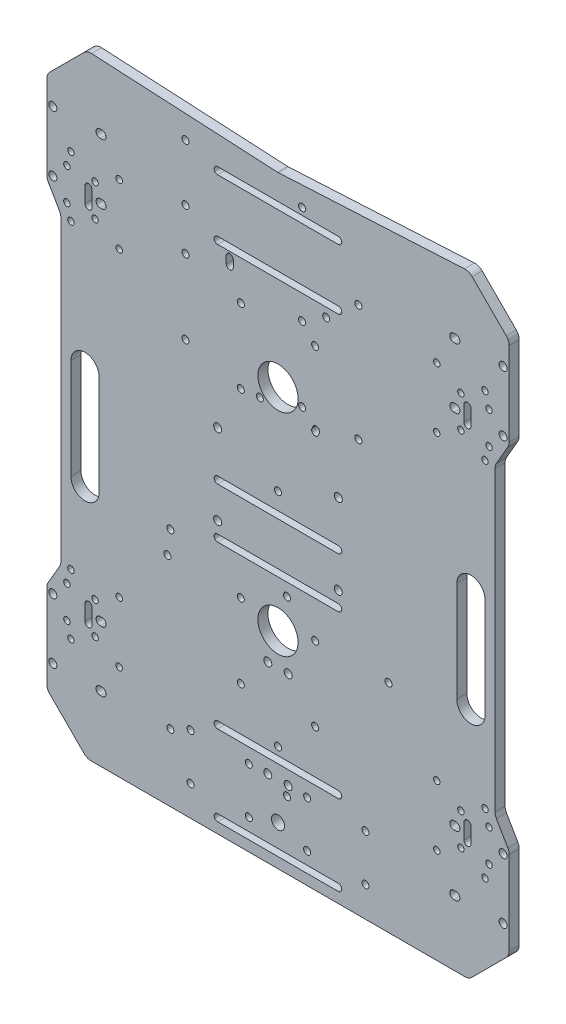
SolidWorks part; units mm, degrees
material "PMMA"
ref_plane "前视基准面" through (0, 0, 0) normal (0, 0, 1) x (1, 0, 0)
ref_plane "上视基准面" through (0, 0, 0) normal (0, 1, 0) x (1, 0, 0)
ref_plane "右视基准面" through (0, 0, 0) normal (1, 0, 0) x (0, 0, -1)
sketch "草图1" plane through (0, 0, 0) normal (0, 0, 1) x (1, 0, 0)
  line L0 (87.5, -88) -> (88.5, -88)
  line L1 (88.5, -92) -> (87.5, -92)
  line L2 (87.5, -118) -> (88.5, -118)
  line L3 (88.5, -122) -> (87.5, -122)
  line L4 (-87.5, -88) -> (-88.5, -88)
  line L5 (-88.5, -92) -> (-87.5, -92)
  line L6 (-87.5, -118) -> (-88.5, -118)
  line L7 (-88.5, -122) -> (-87.5, -122)
  line L8 (-87.5, 88) -> (-88.5, 88)
  line L9 (-88.5, 92) -> (-87.5, 92)
  line L10 (-87.5, 118) -> (-88.5, 118)
  line L11 (-88.5, 122) -> (-87.5, 122)
  line L12 (30, -26.75) -> (-30, -26.75)
  line L13 (-30, -23.25) -> (30, -23.25)
  line L14 (30, 131.5) -> (-30, 131.5)
  line L15 (-30, 135) -> (30, 135)
  line L16 (30, -147.25) -> (-30, -147.25)
  line L17 (-30, -143.75) -> (30, -143.75)
  line L18 (30, 101.5) -> (-30, 101.5)
  line L19 (-30, 105) -> (30, 105)
  line L20 (30, -1.75) -> (-30, -1.75)
  line L21 (-30, 1.75) -> (30, 1.75)
  line L22 (30, -107.25) -> (-30, -107.25)
  line L23 (-30, -103.75) -> (30, -103.75)
  line L24 (-25.75, 95.308) -> (-25.75, 98.808)
  line L25 (-22.25, 98.808) -> (-22.25, 95.308)
  line L26 (-89, 15) -> (-89, -35)
  line L27 (-103, -35) -> (-103, 15)
  line L28 (-96, -86.1) -> (-96, -93.9)
  line L29 (-92.5, -93.9) -> (-92.5, -86.1)
  line L30 (-96, 93.9) -> (-96, 86.1)
  line L31 (-92.5, 86.1) -> (-92.5, 93.9)
  line L32 (96, -86.1) -> (96, -93.9)
  line L33 (92.5, -93.9) -> (92.5, -86.1)
  line L34 (96, 93.9) -> (96, 86.1)
  line L35 (92.5, 86.1) -> (92.5, 93.9)
  line L36 (113.5355, -133.9645) -> (96.4645, -151.0355)
  line L37 (92.9289, -152.5) -> (-92.9289, -152.5)
  line L38 (-96.4645, -151.0355) -> (-113.5355, -133.9645)
  line L39 (-115, -130.4289) -> (-115, -88.8397)
  line L40 (-108.6699, -76.5359) -> (-114.3301, -86.3397)
  line L41 (-108, 74.0359) -> (-108, -74.0359)
  line L42 (-114.3301, 86.3397) -> (-108.6699, 76.5359)
  line L43 (-115, 88.8397) -> (-115, 130.4289)
  line L44 (-113.5355, 133.9645) -> (-96.5746, 150.9254)
  line L45 (-0.2628, 147.5138) -> (-92.7763, 152.383)
  line L46 (92.7763, 152.383) -> (0.2628, 147.5138)
  line L47 (96.5746, 150.9254) -> (113.5355, 133.9645)
  line L48 (115, 130.4289) -> (115, 88.8397)
  line L49 (114.3301, 86.3397) -> (108.6699, 76.5359)
  line L50 (108, 74.0359) -> (108, -74.0359)
  line L51 (108.6699, -76.5359) -> (114.3301, -86.3397)
  line L52 (115, -88.8397) -> (115, -130.4289)
  line L53 (89, 15) -> (89, -35)
  line L54 (103, -35) -> (103, 15)
  line L55 (87.5, 118) -> (88.5, 118)
  line L56 (88.5, 122) -> (87.5, 122)
  line L57 (87.5, 88) -> (88.5, 88)
  line L58 (88.5, 92) -> (87.5, 92)
  arc A0 (112, -118) -> (112, -122) centre (112, -120) cw
  arc A1 (112, -122) -> (112, -118) centre (112, -120) cw
  arc A2 (88.5, -88) -> (88.5, -92) centre (88.5, -90) cw
  arc A3 (87.5, -92) -> (87.5, -88) centre (87.5, -90) cw
  arc A4 (88.5, -118) -> (88.5, -122) centre (88.5, -120) cw
  arc A5 (87.5, -122) -> (87.5, -118) centre (87.5, -120) cw
  arc A6 (112, -88) -> (112, -92) centre (112, -90) cw
  arc A7 (112, -92) -> (112, -88) centre (112, -90) cw
  arc A8 (-88.5, -88) -> (-88.5, -92) centre (-88.5, -90) ccw
  arc A9 (-87.5, -92) -> (-87.5, -88) centre (-87.5, -90) ccw
  arc A10 (-88.5, -118) -> (-88.5, -122) centre (-88.5, -120) ccw
  arc A11 (-87.5, -122) -> (-87.5, -118) centre (-87.5, -120) ccw
  arc A12 (112, 122) -> (112, 118) centre (112, 120) ccw
  arc A13 (112, 118) -> (112, 122) centre (112, 120) ccw
  arc A14 (112, 92) -> (112, 88) centre (112, 90) ccw
  arc A15 (112, 88) -> (112, 92) centre (112, 90) ccw
  arc A16 (-112, 122) -> (-112, 118) centre (-112, 120) cw
  arc A17 (-112, 118) -> (-112, 122) centre (-112, 120) cw
  arc A18 (-88.5, 88) -> (-88.5, 92) centre (-88.5, 90) cw
  arc A19 (-87.5, 92) -> (-87.5, 88) centre (-87.5, 90) cw
  arc A20 (-88.5, 118) -> (-88.5, 122) centre (-88.5, 120) cw
  arc A21 (-87.5, 122) -> (-87.5, 118) centre (-87.5, 120) cw
  arc A22 (-112, 92) -> (-112, 88) centre (-112, 90) cw
  arc A23 (-112, 88) -> (-112, 92) centre (-112, 90) cw
  arc A24 (0, -129.25) -> (0, -135.75) centre (0, -132.5) cw
  arc A25 (0, -135.75) -> (0, -129.25) centre (0, -132.5) cw
  arc A26 (-30, -26.75) -> (-30, -23.25) centre (-30, -25) cw
  arc A27 (30, -23.25) -> (30, -26.75) centre (30, -25) cw
  arc A28 (-30, 131.5) -> (-30, 135) centre (-30, 133.25) cw
  arc A29 (30, 135) -> (30, 131.5) centre (30, 133.25) cw
  arc A30 (-30, -147.25) -> (-30, -143.75) centre (-30, -145.5) cw
  arc A31 (30, -143.75) -> (30, -147.25) centre (30, -145.5) cw
  arc A32 (-30, 101.5) -> (-30, 105) centre (-30, 103.25) cw
  arc A33 (30, 105) -> (30, 101.5) centre (30, 103.25) cw
  arc A34 (-30, -1.75) -> (-30, 1.75) centre (-30, 0) cw
  arc A35 (30, 1.75) -> (30, -1.75) centre (30, 0) cw
  arc A36 (-30, -107.25) -> (-30, -103.75) centre (-30, -105.5) cw
  arc A37 (30, -103.75) -> (30, -107.25) centre (30, -105.5) cw
  arc A38 (55, -43.08) -> (55, -46.58) centre (55, -44.83) cw
  arc A39 (55, -46.58) -> (55, -43.08) centre (55, -44.83) cw
  arc A40 (0, 11.92) -> (0, 8.42) centre (0, 10.17) cw
  arc A41 (0, 8.42) -> (0, 11.92) centre (0, 10.17) cw
  arc A42 (-55, -43.08) -> (-55, -46.58) centre (-55, -44.83) cw
  arc A43 (-55, -46.58) -> (-55, -43.08) centre (-55, -44.83) cw
  arc A44 (5.075, -63.9) -> (5.075, -67.9) centre (5.075, -65.9) cw
  arc A45 (5.075, -67.9) -> (5.075, -63.9) centre (5.075, -65.9) cw
  arc A46 (-5.075, -63.9) -> (-5.075, -67.9) centre (-5.075, -65.9) cw
  arc A47 (-5.075, -67.9) -> (-5.075, -63.9) centre (-5.075, -65.9) cw
  arc A48 (-5.075, -112.1) -> (-5.075, -116.1) centre (-5.075, -114.1) cw
  arc A49 (-5.075, -116.1) -> (-5.075, -112.1) centre (-5.075, -114.1) cw
  arc A50 (5.075, -112.1) -> (5.075, -116.1) centre (5.075, -114.1) cw
  arc A51 (5.075, -116.1) -> (5.075, -112.1) centre (5.075, -114.1) cw
  arc A52 (0, -98.08) -> (0, -101.58) centre (0, -99.83) cw
  arc A53 (0, -101.58) -> (0, -98.08) centre (0, -99.83) cw
  arc A54 (-43.5, -112.75) -> (-43.5, -116.25) centre (-43.5, -114.5) cw
  arc A55 (-43.5, -116.25) -> (-43.5, -112.75) centre (-43.5, -114.5) cw
  arc A56 (43.5, -112.75) -> (43.5, -116.25) centre (43.5, -114.5) cw
  arc A57 (43.5, -116.25) -> (43.5, -112.75) centre (43.5, -114.5) cw
  arc A58 (-43.5, -135.75) -> (-43.5, -139.25) centre (-43.5, -137.5) cw
  arc A59 (-43.5, -139.25) -> (-43.5, -135.75) centre (-43.5, -137.5) cw
  arc A60 (43.5, -135.75) -> (43.5, -139.25) centre (43.5, -137.5) cw
  arc A61 (43.5, -139.25) -> (43.5, -135.75) centre (43.5, -137.5) cw
  arc A62 (14.5, -135.75) -> (14.5, -139.25) centre (14.5, -137.5) cw
  arc A63 (14.5, -139.25) -> (14.5, -135.75) centre (14.5, -137.5) cw
  arc A64 (-14.5, -112.75) -> (-14.5, -116.25) centre (-14.5, -114.5) cw
  arc A65 (-14.5, -116.25) -> (-14.5, -112.75) centre (-14.5, -114.5) cw
  arc A66 (14.5, -112.75) -> (14.5, -116.25) centre (14.5, -114.5) cw
  arc A67 (14.5, -116.25) -> (14.5, -112.75) centre (14.5, -114.5) cw
  arc A68 (-14.5, -135.75) -> (-14.5, -139.25) centre (-14.5, -137.5) cw
  arc A69 (-14.5, -139.25) -> (-14.5, -135.75) centre (-14.5, -137.5) cw
  arc A70 (-18.5, 80.25) -> (-18.5, 83.75) centre (-18.5, 82) cw
  arc A71 (-18.5, 83.75) -> (-18.5, 80.25) centre (-18.5, 82) cw
  arc A72 (-18.5, 43.25) -> (-18.5, 46.75) centre (-18.5, 45) cw
  arc A73 (-18.5, 46.75) -> (-18.5, 43.25) centre (-18.5, 45) cw
  arc A74 (18.5, 80.25) -> (18.5, 83.75) centre (18.5, 82) cw
  arc A75 (18.5, 83.75) -> (18.5, 80.25) centre (18.5, 82) cw
  arc A76 (-18.5, -83.75) -> (-18.5, -80.25) centre (-18.5, -82) ccw
  arc A77 (-18.5, -80.25) -> (-18.5, -83.75) centre (-18.5, -82) ccw
  arc A78 (18.5, -46.75) -> (18.5, -43.25) centre (18.5, -45) ccw
  arc A79 (18.5, -43.25) -> (18.5, -46.75) centre (18.5, -45) ccw
  arc A80 (-18.5, -46.75) -> (-18.5, -43.25) centre (-18.5, -45) ccw
  arc A81 (-18.5, -43.25) -> (-18.5, -46.75) centre (-18.5, -45) ccw
  arc A82 (18.5, -83.75) -> (18.5, -80.25) centre (18.5, -82) ccw
  arc A83 (18.5, -80.25) -> (18.5, -83.75) centre (18.5, -82) ccw
  arc A84 (-25.75, 98.808) -> (-24, 100.558) centre (-24, 98.808) cw
  arc A85 (-22.25, 95.308) -> (-25.75, 95.308) centre (-24, 95.308) cw
  arc A86 (-24, 100.558) -> (-22.25, 98.808) centre (-24, 98.808) cw
  arc A87 (17.2588, 46.2337) -> (19, 47.808) centre (19, 46.058) cw
  arc A88 (18.5, 43.25) -> (17.2588, 46.2337) centre (18.5, 45) cw
  arc A89 (20.2412, 44.8243) -> (18.5, 43.25) centre (18.5, 45) cw
  arc A90 (19, 47.808) -> (20.2412, 44.8243) centre (19, 46.058) cw
  arc A91 (-9, 47.808) -> (-9, 44.308) centre (-9, 46.058) cw
  arc A92 (-9, 44.308) -> (-9, 47.808) centre (-9, 46.058) cw
  arc A93 (24, 98.808) -> (24, 95.308) centre (24, 97.058) cw
  arc A94 (24, 95.308) -> (24, 98.808) centre (24, 97.058) cw
  arc A95 (0, -60) -> (0, -40) centre (0, -50) ccw
  arc A96 (0, -40) -> (0, -60) centre (0, -50) ccw
  arc A97 (0, 45) -> (0, 65) centre (0, 55) ccw
  arc A98 (0, 65) -> (0, 45) centre (0, 55) ccw
  arc A99 (-53.5, -31.25) -> (-53.5, -34.75) centre (-53.5, -33) cw
  arc A100 (-53.5, -34.75) -> (-53.5, -31.25) centre (-53.5, -33) cw
  arc A101 (4.5, -31.25) -> (4.5, -34.75) centre (4.5, -33) cw
  arc A102 (4.5, -34.75) -> (4.5, -31.25) centre (4.5, -33) cw
  arc A103 (4.5, -117.25) -> (4.5, -120.75) centre (4.5, -119) cw
  arc A104 (4.5, -120.75) -> (4.5, -117.25) centre (4.5, -119) cw
  arc A105 (-53.5, -117.25) -> (-53.5, -120.75) centre (-53.5, -119) cw
  arc A106 (-53.5, -120.75) -> (-53.5, -117.25) centre (-53.5, -119) cw
  arc A107 (-89, -35) -> (-103, -35) centre (-96, -35) cw
  arc A108 (-96, 22) -> (-89, 15) centre (-96, 15) cw
  arc A109 (-103, 15) -> (-96, 22) centre (-96, 15) cw
  arc A110 (12, 91.25) -> (12, 87.75) centre (12, 89.5) cw
  arc A111 (12, 87.75) -> (12, 91.25) centre (12, 89.5) cw
  arc A112 (-46, 91.25) -> (-46, 87.75) centre (-46, 89.5) cw
  arc A113 (-46, 87.75) -> (-46, 91.25) centre (-46, 89.5) cw
  arc A114 (12, 140.25) -> (12, 136.75) centre (12, 138.5) cw
  arc A115 (12, 136.75) -> (12, 140.25) centre (12, 138.5) cw
  arc A116 (-46, 140.25) -> (-46, 136.75) centre (-46, 138.5) cw
  arc A117 (-46, 136.75) -> (-46, 140.25) centre (-46, 138.5) cw
  arc A118 (40, 54.25) -> (40, 50.75) centre (40, 52.5) cw
  arc A119 (40, 50.75) -> (40, 54.25) centre (40, 52.5) cw
  arc A120 (-46, 112.25) -> (-46, 108.75) centre (-46, 110.5) cw
  arc A121 (-46, 108.75) -> (-46, 112.25) centre (-46, 110.5) cw
  arc A122 (40, 112.25) -> (40, 108.75) centre (40, 110.5) cw
  arc A123 (40, 108.75) -> (40, 112.25) centre (40, 110.5) cw
  arc A124 (12, 54.25) -> (12, 50.75) centre (12, 52.5) cw
  arc A125 (12, 50.75) -> (12, 54.25) centre (12, 52.5) cw
  arc A126 (-46, 54.25) -> (-46, 50.75) centre (-46, 52.5) cw
  arc A127 (-46, 50.75) -> (-46, 54.25) centre (-46, 52.5) cw
  arc A128 (30, -15.5) -> (30, -19.5) centre (30, -17.5) cw
  arc A129 (30, -19.5) -> (30, -15.5) centre (30, -17.5) cw
  arc A130 (-30, 24.5) -> (-30, 20.5) centre (-30, 22.5) cw
  arc A131 (-30, 20.5) -> (-30, 24.5) centre (-30, 22.5) cw
  arc A132 (30, 24.5) -> (30, 20.5) centre (30, 22.5) cw
  arc A133 (30, 20.5) -> (30, 24.5) centre (30, 22.5) cw
  arc A134 (-30, -15.5) -> (-30, -19.5) centre (-30, -17.5) cw
  arc A135 (-30, -19.5) -> (-30, -15.5) centre (-30, -17.5) cw
  arc A136 (-91, -96.4) -> (-91, -99.6) centre (-91, -98) ccw
  arc A137 (-91, -99.6) -> (-91, -96.4) centre (-91, -98) ccw
  arc A138 (-91, -80.4) -> (-91, -83.6) centre (-91, -82) ccw
  arc A139 (-91, -83.6) -> (-91, -80.4) centre (-91, -82) ccw
  arc A140 (-105, -80.4) -> (-105, -83.6) centre (-105, -82) ccw
  arc A141 (-105, -83.6) -> (-105, -80.4) centre (-105, -82) ccw
  arc A142 (-96, -93.9) -> (-92.5, -93.9) centre (-94.25, -93.9) ccw
  arc A143 (-92.5, -86.1) -> (-94.25, -84.35) centre (-94.25, -86.1) ccw
  arc A144 (-94.25, -84.35) -> (-96, -86.1) centre (-94.25, -86.1) ccw
  arc A145 (-79, -103.4) -> (-79, -106.6) centre (-79, -105) ccw
  arc A146 (-79, -106.6) -> (-79, -103.4) centre (-79, -105) ccw
  arc A147 (-103, -73.4) -> (-103, -76.6) centre (-103, -75) ccw
  arc A148 (-103, -76.6) -> (-103, -73.4) centre (-103, -75) ccw
  arc A149 (-103, -103.4) -> (-103, -106.6) centre (-103, -105) ccw
  arc A150 (-103, -106.6) -> (-103, -103.4) centre (-103, -105) ccw
  arc A151 (-105, -96.4) -> (-105, -99.6) centre (-105, -98) ccw
  arc A152 (-105, -99.6) -> (-105, -96.4) centre (-105, -98) ccw
  arc A153 (-79, -73.4) -> (-79, -76.6) centre (-79, -75) ccw
  arc A154 (-79, -76.6) -> (-79, -73.4) centre (-79, -75) ccw
  arc A155 (-91, 83.6) -> (-91, 80.4) centre (-91, 82) ccw
  arc A156 (-91, 80.4) -> (-91, 83.6) centre (-91, 82) ccw
  arc A157 (-91, 99.6) -> (-91, 96.4) centre (-91, 98) ccw
  arc A158 (-91, 96.4) -> (-91, 99.6) centre (-91, 98) ccw
  arc A159 (-105, 99.6) -> (-105, 96.4) centre (-105, 98) ccw
  arc A160 (-105, 96.4) -> (-105, 99.6) centre (-105, 98) ccw
  arc A161 (-96, 86.1) -> (-92.5, 86.1) centre (-94.25, 86.1) ccw
  arc A162 (-92.5, 93.9) -> (-94.25, 95.65) centre (-94.25, 93.9) ccw
  arc A163 (-94.25, 95.65) -> (-96, 93.9) centre (-94.25, 93.9) ccw
  arc A164 (-79, 76.6) -> (-79, 73.4) centre (-79, 75) ccw
  arc A165 (-79, 73.4) -> (-79, 76.6) centre (-79, 75) ccw
  arc A166 (-103, 106.6) -> (-103, 103.4) centre (-103, 105) ccw
  arc A167 (-103, 103.4) -> (-103, 106.6) centre (-103, 105) ccw
  arc A168 (-103, 76.6) -> (-103, 73.4) centre (-103, 75) ccw
  arc A169 (-103, 73.4) -> (-103, 76.6) centre (-103, 75) ccw
  arc A170 (-105, 83.6) -> (-105, 80.4) centre (-105, 82) ccw
  arc A171 (-105, 80.4) -> (-105, 83.6) centre (-105, 82) ccw
  arc A172 (-79, 106.6) -> (-79, 103.4) centre (-79, 105) ccw
  arc A173 (-79, 103.4) -> (-79, 106.6) centre (-79, 105) ccw
  arc A174 (91, -96.4) -> (91, -99.6) centre (91, -98) cw
  arc A175 (91, -99.6) -> (91, -96.4) centre (91, -98) cw
  arc A176 (91, -80.4) -> (91, -83.6) centre (91, -82) cw
  arc A177 (91, -83.6) -> (91, -80.4) centre (91, -82) cw
  arc A178 (105, -80.4) -> (105, -83.6) centre (105, -82) cw
  arc A179 (105, -83.6) -> (105, -80.4) centre (105, -82) cw
  arc A180 (96, -93.9) -> (92.5, -93.9) centre (94.25, -93.9) cw
  arc A181 (94.25, -84.35) -> (96, -86.1) centre (94.25, -86.1) cw
  arc A182 (92.5, -86.1) -> (94.25, -84.35) centre (94.25, -86.1) cw
  arc A183 (79, -103.4) -> (79, -106.6) centre (79, -105) cw
  arc A184 (79, -106.6) -> (79, -103.4) centre (79, -105) cw
  arc A185 (103, -73.4) -> (103, -76.6) centre (103, -75) cw
  arc A186 (103, -76.6) -> (103, -73.4) centre (103, -75) cw
  arc A187 (103, -103.4) -> (103, -106.6) centre (103, -105) cw
  arc A188 (103, -106.6) -> (103, -103.4) centre (103, -105) cw
  arc A189 (105, -96.4) -> (105, -99.6) centre (105, -98) cw
  arc A190 (105, -99.6) -> (105, -96.4) centre (105, -98) cw
  arc A191 (79, -73.4) -> (79, -76.6) centre (79, -75) cw
  arc A192 (79, -76.6) -> (79, -73.4) centre (79, -75) cw
  arc A193 (91, 83.6) -> (91, 80.4) centre (91, 82) cw
  arc A194 (91, 80.4) -> (91, 83.6) centre (91, 82) cw
  arc A195 (91, 99.6) -> (91, 96.4) centre (91, 98) cw
  arc A196 (91, 96.4) -> (91, 99.6) centre (91, 98) cw
  arc A197 (105, 99.6) -> (105, 96.4) centre (105, 98) cw
  arc A198 (105, 96.4) -> (105, 99.6) centre (105, 98) cw
  arc A199 (96, 86.1) -> (92.5, 86.1) centre (94.25, 86.1) cw
  arc A200 (94.25, 95.65) -> (96, 93.9) centre (94.25, 93.9) cw
  arc A201 (92.5, 93.9) -> (94.25, 95.65) centre (94.25, 93.9) cw
  arc A202 (79, 76.6) -> (79, 73.4) centre (79, 75) cw
  arc A203 (79, 73.4) -> (79, 76.6) centre (79, 75) cw
  arc A204 (103, 106.6) -> (103, 103.4) centre (103, 105) cw
  arc A205 (103, 103.4) -> (103, 106.6) centre (103, 105) cw
  arc A206 (103, 76.6) -> (103, 73.4) centre (103, 75) cw
  arc A207 (103, 73.4) -> (103, 76.6) centre (103, 75) cw
  arc A208 (105, 83.6) -> (105, 80.4) centre (105, 82) cw
  arc A209 (105, 80.4) -> (105, 83.6) centre (105, 82) cw
  arc A210 (79, 106.6) -> (79, 103.4) centre (79, 105) cw
  arc A211 (79, 103.4) -> (79, 106.6) centre (79, 105) cw
  arc A212 (96.4645, -151.0355) -> (92.9289, -152.5) centre (92.9289, -147.5) cw
  arc A213 (-92.9289, -152.5) -> (-96.4645, -151.0355) centre (-92.9289, -147.5) cw
  arc A214 (-113.5355, -133.9645) -> (-115, -130.4289) centre (-110, -130.4289) cw
  arc A215 (-115, -88.8397) -> (-114.3301, -86.3397) centre (-110, -88.8397) cw
  arc A216 (-108.6699, -76.5359) -> (-108, -74.0359) centre (-113, -74.0359) ccw
  arc A217 (-108, 74.0359) -> (-108.6699, 76.5359) centre (-113, 74.0359) ccw
  arc A218 (-114.3301, 86.3397) -> (-115, 88.8397) centre (-110, 88.8397) cw
  arc A219 (-115, 130.4289) -> (-113.5355, 133.9645) centre (-110, 130.4289) cw
  arc A220 (-96.5746, 150.9254) -> (-93.0391, 152.3899) centre (-93.0391, 147.3899) cw
  arc A221 (-93.0391, 152.3899) -> (-92.7763, 152.383) centre (-93.0391, 147.3899) cw
  arc A222 (-0.2628, 147.5138) -> (0, 147.5069) centre (0, 152.5069) ccw
  arc A223 (0, 147.5069) -> (0.2628, 147.5138) centre (0, 152.5069) ccw
  arc A224 (92.7763, 152.383) -> (96.5746, 150.9254) centre (93.0391, 147.3899) cw
  arc A225 (113.5355, 133.9645) -> (115, 130.4289) centre (110, 130.4289) cw
  arc A226 (115, 88.8397) -> (114.3301, 86.3397) centre (110, 88.8397) cw
  arc A227 (108.6699, 76.5359) -> (108, 74.0359) centre (113, 74.0359) ccw
  arc A228 (108, -74.0359) -> (108.6699, -76.5359) centre (113, -74.0359) ccw
  arc A229 (114.3301, -86.3397) -> (115, -88.8397) centre (110, -88.8397) cw
  arc A230 (115, -130.4289) -> (113.5355, -133.9645) centre (110, -130.4289) cw
  arc A231 (89, -35) -> (103, -35) centre (96, -35) ccw
  arc A232 (103, 15) -> (96, 22) centre (96, 15) ccw
  arc A233 (96, 22) -> (89, 15) centre (96, 15) ccw
  arc A234 (88.5, 118) -> (88.5, 122) centre (88.5, 120) ccw
  arc A235 (87.5, 122) -> (87.5, 118) centre (87.5, 120) ccw
  arc A236 (88.5, 88) -> (88.5, 92) centre (88.5, 90) ccw
  arc A237 (87.5, 92) -> (87.5, 88) centre (87.5, 90) ccw
  arc A238 (-112, -88) -> (-112, -92) centre (-112, -90) ccw
  arc A239 (-112, -92) -> (-112, -88) centre (-112, -90) ccw
  arc A240 (-112, -118) -> (-112, -122) centre (-112, -120) ccw
  arc A241 (-112, -122) -> (-112, -118) centre (-112, -120) ccw
  dimension "D1" = 2
  dimension "D2" = 3.25
  dimension "D3" = 1.75
  dimension "D4" = 10
  dimension "D5" = 7
  dimension "D6" = 1.6
  dimension "D7" = 5
  dimension "D8" = 0.2628
  dimension "D9" = 4.5
  dimension "D10" = 5.075
  dimension "D11" = 12
  dimension "D12" = 14.5
  dimension "D13" = 17.2588
  dimension "D14" = 18.5
  dimension "D15" = 19
  dimension "D16" = 30
  dimension "D17" = 24
  dimension "D18" = 87.5
  dimension "D19" = 40
  dimension "D20" = 43.5
  dimension "D21" = 55
  dimension "D22" = 79
  dimension "D23" = 88.5
  dimension "D24" = 89
  dimension "D25" = 92.7763
  dimension "D26" = 91
  dimension "D27" = 92.9289
  dimension "D28" = 96.4645
  dimension "D29" = 108
  dimension "D30" = 108.6699
  dimension "D31" = 110
  dimension "D32" = 22.25
  dimension "D33" = 30
  dimension "D34" = 87.5
  dimension "D35" = 89
  dimension "D36" = 105
  dimension "D37" = 10.17
  dimension "D38" = 22
  dimension "D39" = 22.5
  dimension "D40" = 112
  dimension "D41" = 44.8243
  dimension "D42" = 74.0359
  dimension "D43" = 86.1
  dimension "D44" = 95.65
  dimension "D45" = 52.5
  dimension "D46" = 5.075
  dimension "D47" = 9
  dimension "D48" = 14.5
  dimension "D49" = 18.5
  dimension "D50" = 97.058
  dimension "D51" = 103.25
  dimension "D52" = 75
  dimension "D53" = 130.4289
  dimension "D54" = 43.5
  dimension "D55" = 46
  dimension "D56" = 53.5
  dimension "D57" = 55
  dimension "D58" = 79
  dimension "D59" = 82
  dimension "D60" = 74.0359
  dimension "D61" = 84.35
  dimension "D62" = 91
  dimension "D63" = 132.5
  dimension "D64" = 89.5
  dimension "D65" = 90
  dimension "D68" = 98
  dimension "D72" = 105
  dimension "D73" = 110.5
  dimension "D74" = 120
  dimension "D76" = 112
  dimension "D77" = 133.25
  dimension "D79" = 138.5
  dimension "D87" = 17.5
  dimension "D88" = 25
  dimension "D89" = 33
  dimension "D90" = 35
  dimension "D91" = 44.83
  dimension "D92" = 45
  dimension "D93" = 50
  dimension "D94" = 65.9
  dimension "D96" = 75
  dimension "D98" = 82
  dimension "D102" = 90
  dimension "D104" = 98
  dimension "D105" = 99.83
  dimension "D106" = 105
  dimension "D107" = 105.5
  dimension "D108" = 114.1
  dimension "D109" = 114.5
  dimension "D110" = 119
  dimension "D111" = 120
  dimension "D116" = 145.5
extrude "亚克力板厚5mm" add sketch "草图1" along normal blind 5
